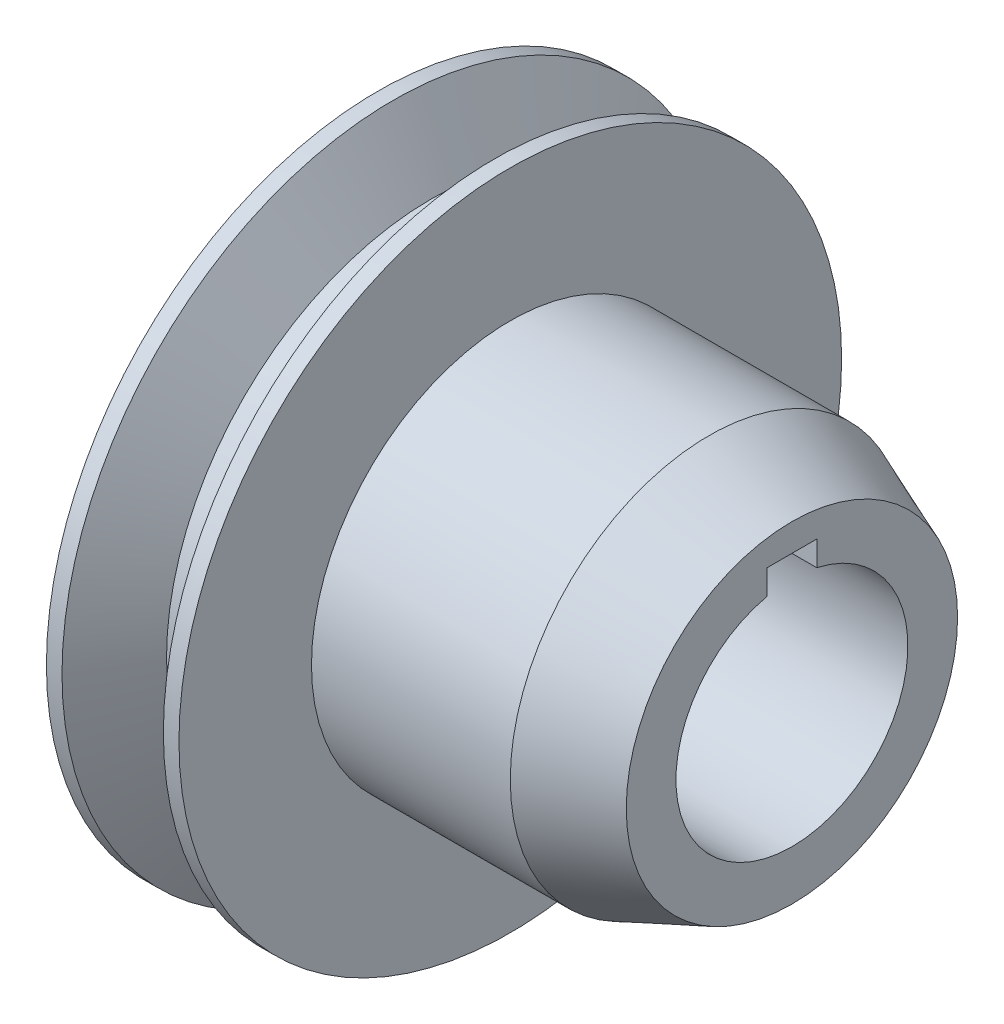
SolidWorks part; units mm, degrees
ref_plane "Front Plane" through (0, 0, 0) normal (0, 0, 1) x (1, 0, 0)
ref_plane "Top Plane" through (0, 0, 0) normal (0, 1, 0) x (1, 0, 0)
ref_plane "Right Plane" through (0, 0, 0) normal (1, 0, 0) x (0, 0, -1)
sketch "Sketch1" plane through (0, 0, 0) normal (0, 0, 1) x (1, 0, 0)
  line L0 (0, 0) -> (0, 16) construction
  line L1 (0.75, 16) -> (-0.75, 16)
  line L2 (-0.75, 16) -> (-3.0594, 20)
  line L3 (-3.0594, 20) -> (-4, 20)
  line L4 (-4, 20) -> (-4, 0)
  line L5 (-4, 0) -> (4, 0)
  line L6 (-19.7925, 0) -> (0, 0) construction
  line L7 (0, 0) -> (0, 26.7449) construction
  line L8 (4, 20) -> (4, 0) construction
  line L9 (3.0594, 20) -> (4, 20)
  line L10 (0.75, 16) -> (3.0594, 20)
  line L11 (4, 12) -> (16, 12)
  line L12 (16, 12) -> (21, 10)
  line L13 (21, 10) -> (21, 0)
  line L14 (21, 0) -> (4, 0)
  line L15 (4, 20) -> (4, 12)
  dimension "D1" = 40
  dimension "D2" = 32
  dimension "D3" = 1.5
  dimension "D4" = 60
  dimension "D5" = 8
  dimension "D6" = 12
  dimension "D7" = 5
  dimension "D8" = 20
  dimension "D9" = 24
revolve "Revolve1" add sketch "Sketch1" angle 360 about L6
sketch "Sketch2" plane through (-4, 0, 0) normal (-1, 0, 0) x (0, 0, 1)
  line L1 (-1.5, 8.3374) -> (1.5, 8.3374)
  line L2 (-1.5, 8.3374) -> (-1.5, 6.8374)
  line L4 (1.5, 8.3374) -> (1.5, 6.8374)
  arc A0 (-1.5, 6.8374) -> (1.5, 6.8374) centre (0, 0) ccw
  point P7 (0, 0)
  point P8 (0, 8.3374)
  dimension "D1" = 14
  dimension "D2" = 1.5
  dimension "D3" = 3
extrude "Cut-Extrude1" cut sketch "Sketch2" against normal through all
